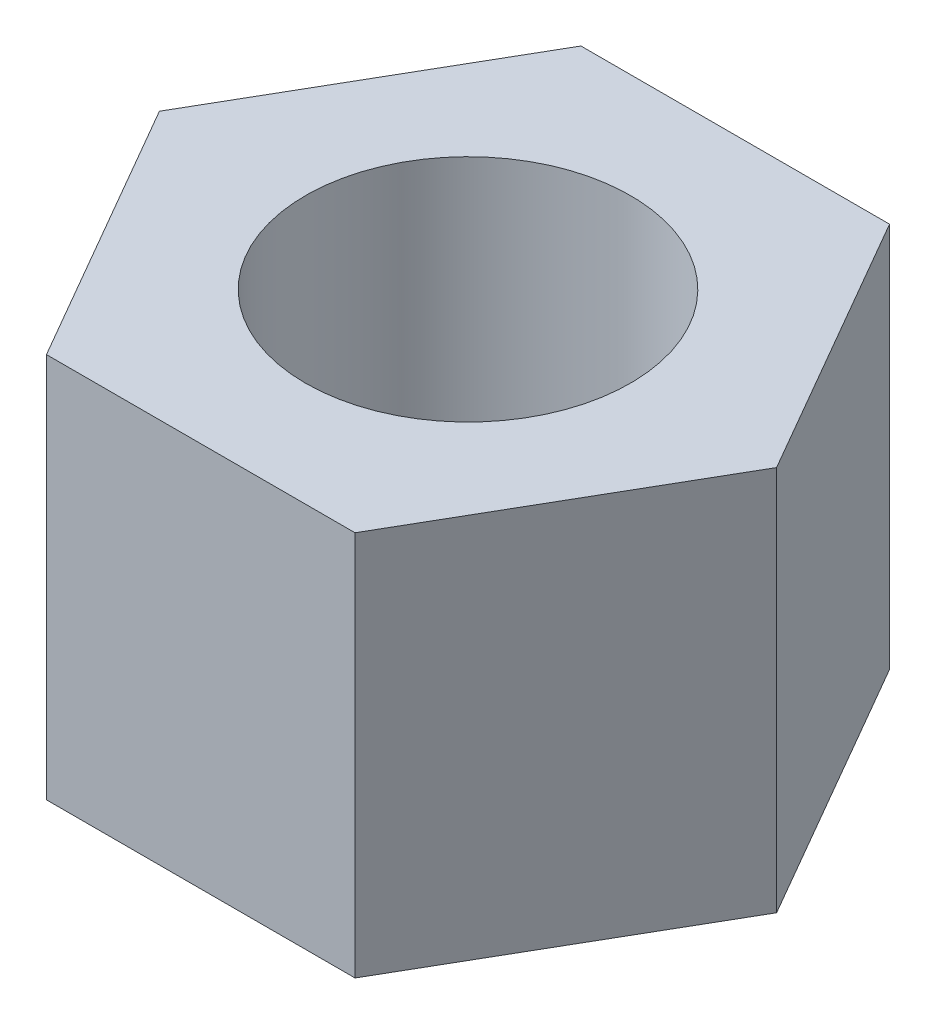
SolidWorks part; units mm, degrees
ref_plane "Płaszczyzna przednia" through (0, 0, 0) normal (0, 0, 1) x (1, 0, 0)
ref_plane "Płaszczyzna górna" through (0, 0, 0) normal (0, 1, 0) x (1, 0, 0)
ref_plane "Płaszczyzna prawa" through (0, 0, 0) normal (1, 0, 0) x (0, 0, -1)
sketch "Szkic1" plane through (0, 0, 0) normal (0, 1, 0) x (1, 0, 0)
  line L1 (8.0031, 0) -> (4.0016, 6.9309)
  line L2 (4.0016, 6.9309) -> (-4.0016, 6.9309)
  line L3 (-4.0016, 6.9309) -> (-8.0031, 0)
  line L4 (-8.0031, 0) -> (-4.0016, -6.9309)
  line L5 (-4.0016, -6.9309) -> (4.0016, -6.9309)
  line L6 (4.0016, -6.9309) -> (8.0031, 0)
  circle A0 centre (0, 0) radius 4.215
  circle A1 centre (0, 0) radius 6.9309 construction
  dimension "D1" = 8.43
extrude "Dodanie-wyciągnięcie1" add sketch "Szkic1" along normal blind 10
